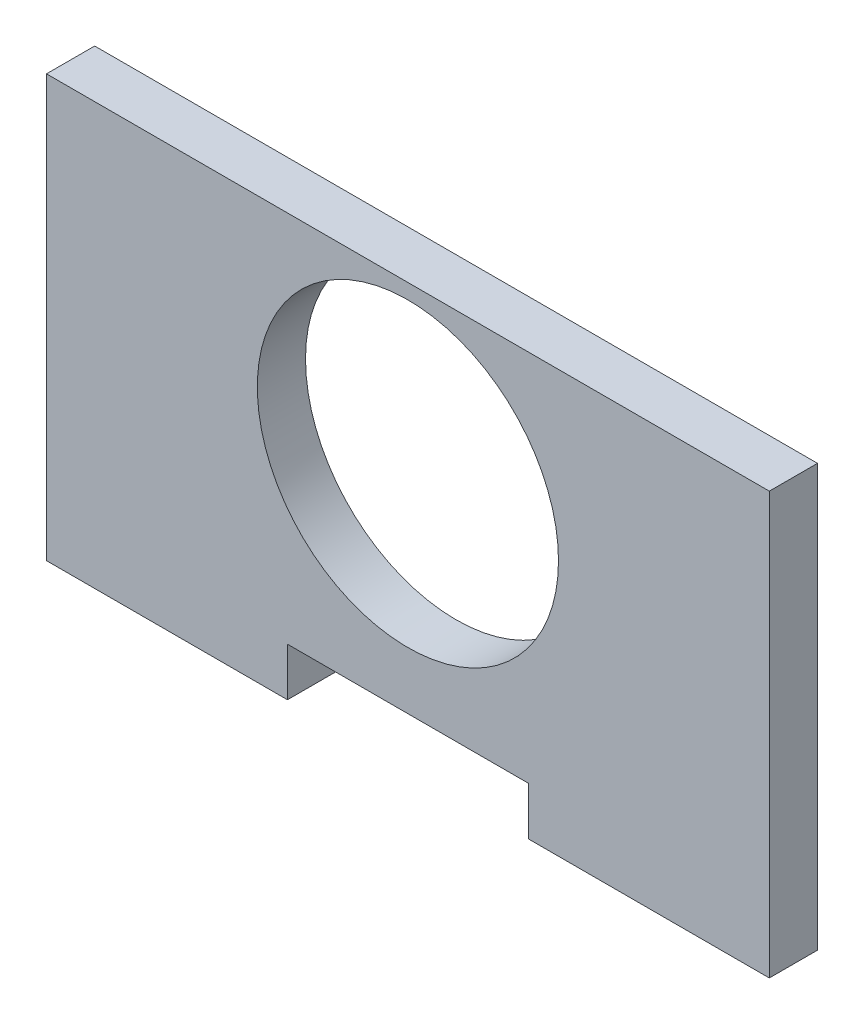
SolidWorks part; units mm, degrees
ref_plane "Front Plane" through (0, 0, 0) normal (0, 0, 1) x (1, 0, 0)
ref_plane "Top Plane" through (0, 0, 0) normal (0, 1, 0) x (1, 0, 0)
ref_plane "Right Plane" through (0, 0, 0) normal (1, 0, 0) x (0, 0, -1)
sketch "Sketch1" plane through (0, 0, 0) normal (0, 0, 1) x (1, 0, 0)
  line L0 (0, 0) -> (0, 22.225) construction
  line L1 (-38.1, -22.225) -> (38.1, -22.225)
  line L2 (-38.1, -22.225) -> (-38.1, 22.225)
  line L3 (-38.1, 22.225) -> (38.1, 22.225)
  line L4 (38.1, -22.225) -> (38.1, 22.225)
  line L5 (-38.1, -22.225) -> (38.1, 22.225) construction
  line L6 (-38.1, 22.225) -> (38.1, -22.225) construction
  point P0 (0, 0)
  dimension "D1" = 76.2
  dimension "D2" = 44.45
extrude "Boss-Extrude1" add sketch "Sketch1" along normal blind 5.08
sketch "Sketch4" plane through (0, 0, 5.08) normal (0, 0, 1) x (1, 0, 0)
  circle A0 centre (0, 4.7625) radius 15.875
  dimension "D1" = 31.75
extrude "Cut-Extrude2" cut sketch "Sketch4" against normal blind 12.7
sketch "Sketch6" plane through (0, -22.225, 0) normal (0, -1, 0) x (1, 0, 0)
  line L15 (-38.1, 0) -> (38.1, 0) construction
  line L16 (-12.7, 0) -> (12.7, 0)
  line L17 (-12.7, 0) -> (-12.7, 5.08)
  line L18 (-12.7, 5.08) -> (12.7, 5.08)
  line L19 (12.7, 0) -> (12.7, 5.08)
  line L20 (-38.1, 5.08) -> (38.1, 5.08) construction
  line L21 (-12.7, 5.08) -> (-38.1, 5.08) construction
  line L22 (12.7, 5.08) -> (38.1, 5.08) construction
  line L23 (12.7, 5.08) -> (38.1, 5.08) construction
extrude "Cut-Extrude4" cut sketch "Sketch6" against normal blind 5.08
equation "\"foamcore\"= .1in"
equation "\"MDF\"= .2in"
equation "\"GMaterial\"= \"MDF\""
equation "\"D1@Cut-Extrude4\"=\"GMaterial\""
equation "\"D1@Boss-Extrude1\"=\"GMaterial\""
